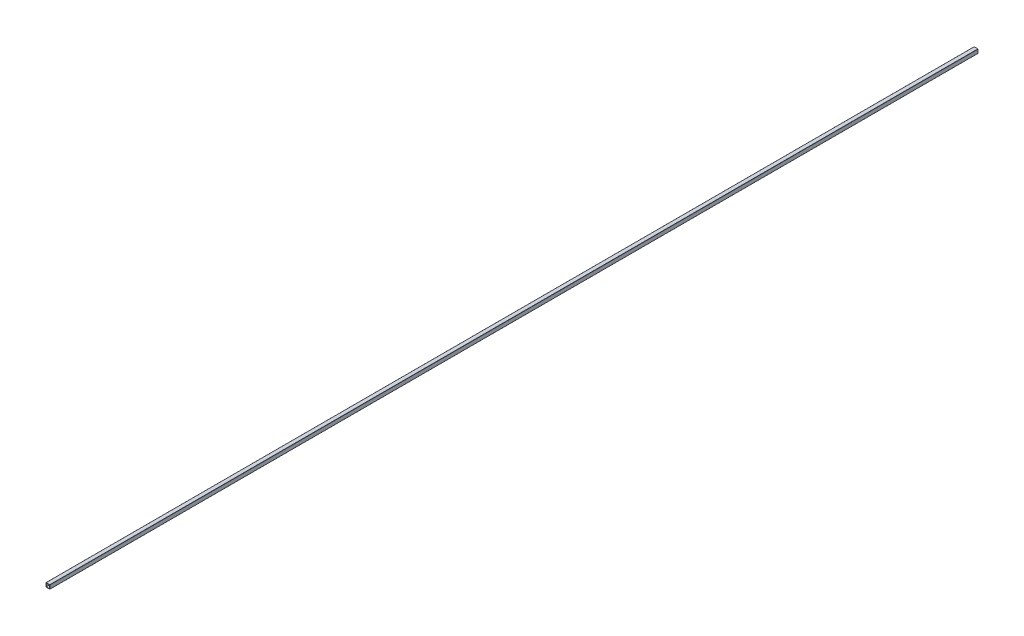
SolidWorks part; units mm, degrees
ref_plane "Alzado" through (0, 0, 0) normal (0, 0, 1) x (1, 0, 0)
ref_plane "Planta" through (0, 0, 0) normal (0, 1, 0) x (1, 0, 0)
ref_plane "Vista lateral" through (0, 0, 0) normal (1, 0, 0) x (0, 0, -1)
sketch "Croquis1" plane through (0, 0, 0) normal (0, 0, 1) x (1, 0, 0)
  line L0 (-10.81, -10.81) -> (-10.81, 10.81)
  line L1 (-11.7, -12.7) -> (11.7, -12.7)
  line L2 (-12.7, -11.7) -> (-12.7, 11.7)
  line L3 (-11.7, 12.7) -> (11.7, 12.7)
  line L4 (12.7, -11.7) -> (12.7, 11.7)
  line L5 (-10.81, 10.81) -> (10.81, 10.81)
  line L6 (10.81, -10.81) -> (10.81, 10.81)
  line L7 (-10.81, -10.81) -> (10.81, -10.81)
  arc A0 (11.7, 12.7) -> (12.7, 11.7) centre (11.7, 11.7) cw
  arc A1 (11.7, -12.7) -> (12.7, -11.7) centre (11.7, -11.7) ccw
  arc A2 (-11.7, -12.7) -> (-12.7, -11.7) centre (-11.7, -11.7) cw
  arc A3 (-12.7, 11.7) -> (-11.7, 12.7) centre (-11.7, 11.7) cw
  arc A4 (-10.81, 10.81) -> (-10.81, 10.81) centre (-10.81, 10.81) cw
  arc A5 (10.81, 10.81) -> (10.81, 10.81) centre (10.81, 10.81) cw
  arc A6 (10.81, -10.81) -> (10.81, -10.81) centre (10.81, -10.81) ccw
  arc A7 (-10.81, -10.81) -> (-10.81, -10.81) centre (-10.81, -10.81) cw
  point P4 (12.7, 0)
  point P6 (0, -12.7)
  point P9 (12.7, 12.7)
  point P12 (12.7, -12.7)
  dimension "D2" = 1
  dimension "D1" = 25.4
  dimension "D3" = 1.89
extrude "Saliente-Extruir1" add sketch "Croquis1" along normal blind 6000
